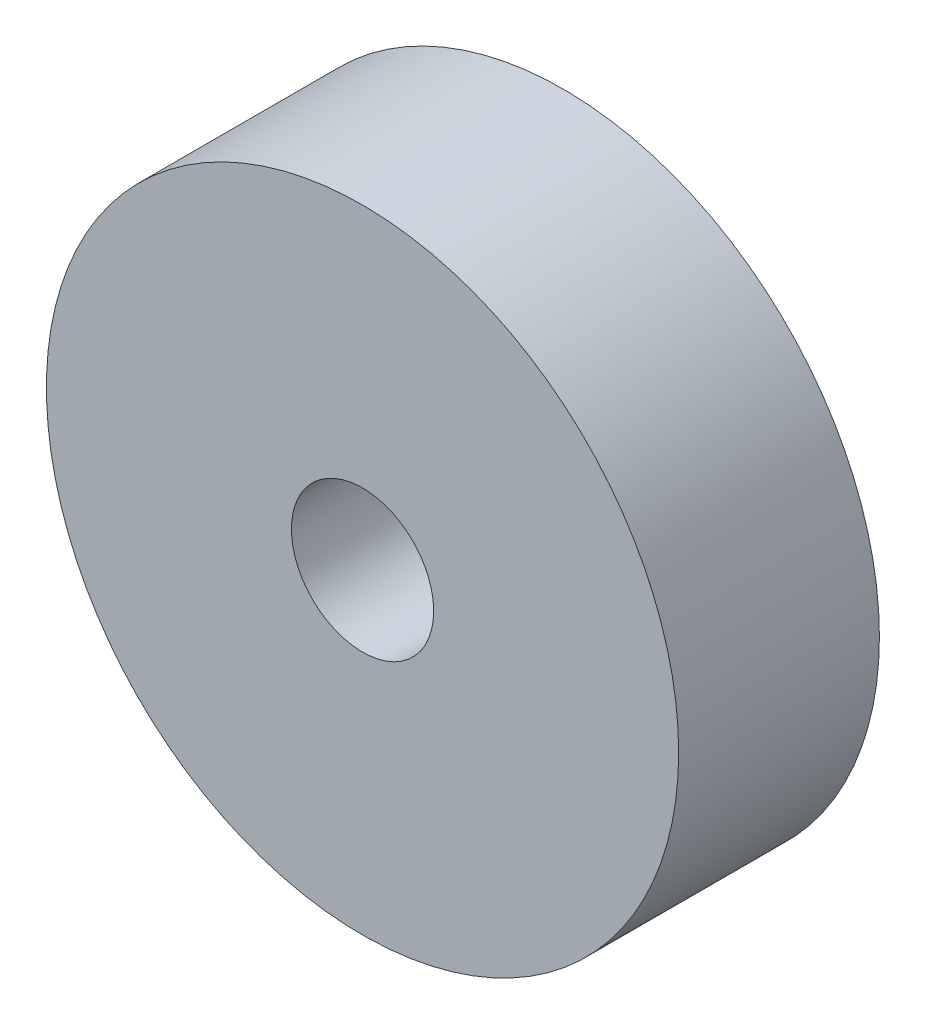
SolidWorks part; units mm, degrees
material "ABS"
ref_plane "Front Plane" through (0, 0, 0) normal (0, 0, 1) x (1, 0, 0)
ref_plane "Top Plane" through (0, 0, 0) normal (0, 1, 0) x (1, 0, 0)
ref_plane "Right Plane" through (0, 0, 0) normal (1, 0, 0) x (0, 0, -1)
sketch "Sketch1" plane through (0, 0, 0) normal (0, 0, 1) x (1, 0, 0)
  circle A0 centre (0, 0) radius 10
  circle A1 centre (0, 0) radius 2.25
  dimension "D1" = 20
  dimension "D2" = 4.5
extrude "Boss-Extrude1" add sketch "Sketch1" along normal blind 6.35
